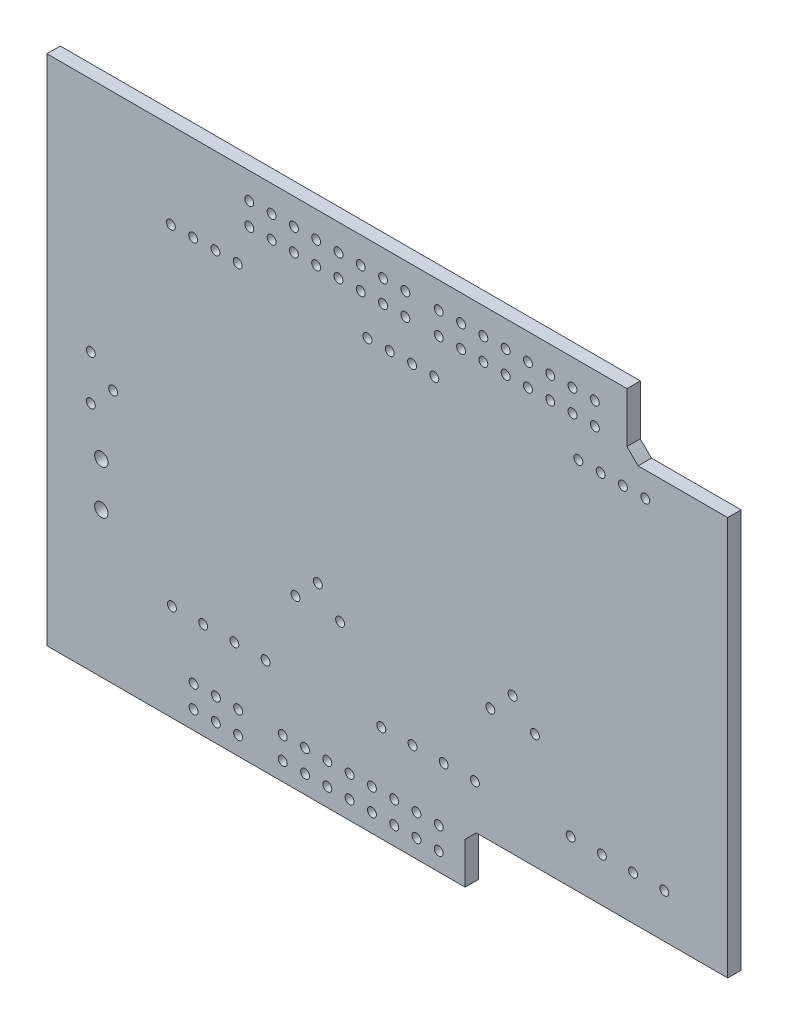
SolidWorks part; units mm, degrees
ref_plane "Front Plane" through (0, 0, 0) normal (0, 0, 1) x (1, 0, 0)
ref_plane "Top Plane" through (0, 0, 0) normal (0, 1, 0) x (1, 0, 0)
ref_plane "Right Plane" through (0, 0, 0) normal (1, 0, 0) x (0, 0, -1)
sketch "Sketch1" plane through (0, 0, 0) normal (0, 0, 1) x (1, 0, 0)
  line L1 (0, 0) -> (77.5716, 0)
  line L2 (0, 0) -> (0, 58.42)
  line L3 (0, 58.42) -> (77.5716, 58.42)
  line L4 (77.5716, 0) -> (77.5716, 58.42)
  dimension "D1" = 77.5716
  dimension "D2" = 58.42
extrude "Boss-Extrude1" add sketch "Sketch1" along normal blind 1.524
sketch "Sketch2" plane through (0, 0, 1.524) normal (0, 0, 1) x (1, 0, 0)
  line L1 (77.5716, 58.42) -> (66.0908, 58.42)
  line L2 (77.5716, 58.42) -> (77.5716, 51.435)
  line L3 (77.5716, 51.435) -> (66.0908, 51.435)
  line L4 (66.0908, 58.42) -> (66.0908, 51.435)
  line L5 (77.5716, 0) -> (47.6504, 0)
  line L6 (77.5716, 0) -> (77.5716, 6)
  line L7 (77.5716, 6) -> (47.6504, 6)
  line L8 (47.6504, 0) -> (47.6504, 6)
  dimension "D1" = 6
  dimension "D2" = 6.985
  dimension "D3" = 11.4808
  dimension "D4" = 29.9212
extrude "Cut-Extrude1" cut sketch "Sketch2" against normal through all
chamfer "Chamfer1" distance 1.27 angle 45 2 edges at (66.0908, 51.435, 0.762) (47.6504, 6, 0.762)
sketch "Sketch3" plane through (0, 0, 1.524) normal (0, 0, 1) x (1, 0, 0)
  line L0 (62.43, 52.88) -> (59.89, 52.88) construction
  line L1 (62.43, 52.88) -> (62.43, 55.42) construction
  line L4 (44.65, 4.62) -> (42.11, 4.62) construction
  line L5 (44.65, 2.08) -> (44.65, 4.62) construction
  line L7 (16.924, 11.2664) -> (11.5748, 10.7736) construction
  line L8 (38.501, 11.2664) -> (37.7002, 10.7664) construction
  line L9 (60.078, 11.2664) -> (59.2772, 10.7664) construction
  line L10 (6.6018, 22.0208) -> (5.8018, 21.0208) construction
  line L11 (5.8018, 21.0208) -> (5.8018, 17.0208) construction
  line L12 (6.6018, 16.0208) -> (5.8018, 17.0208) construction
  line L14 (60.5536, 48.6156) -> (63.0936, 48.6156) construction
  line L15 (14.2494, 11.02) -> (17.8054, 11.02) construction
  circle A0 centre (62.43, 52.88) radius 0.508
  circle A1 centre (59.89, 52.88) radius 0.508
  circle A2 centre (57.35, 52.88) radius 0.508
  circle A3 centre (54.81, 52.88) radius 0.508
  circle A4 centre (52.27, 52.88) radius 0.508
  circle A5 centre (49.73, 52.88) radius 0.508
  circle A6 centre (47.19, 52.88) radius 0.508
  circle A7 centre (44.65, 52.88) radius 0.508
  circle A8 centre (62.43, 55.42) radius 0.508
  circle A9 centre (59.89, 55.42) radius 0.508
  circle A10 centre (57.35, 55.42) radius 0.508
  circle A11 centre (54.81, 55.42) radius 0.508
  circle A12 centre (52.27, 55.42) radius 0.508
  circle A13 centre (49.73, 55.42) radius 0.508
  circle A14 centre (47.19, 55.42) radius 0.508
  circle A15 centre (44.65, 55.42) radius 0.508
  circle A16 centre (40.84, 52.88) radius 0.508
  circle A17 centre (38.3, 52.88) radius 0.508
  circle A18 centre (35.76, 52.88) radius 0.508
  circle A19 centre (33.22, 52.88) radius 0.508
  circle A20 centre (30.68, 52.88) radius 0.508
  circle A21 centre (28.14, 52.88) radius 0.508
  circle A22 centre (25.6, 52.88) radius 0.508
  circle A23 centre (23.06, 52.88) radius 0.508
  circle A24 centre (38.3, 55.42) radius 0.508
  circle A25 centre (35.76, 55.42) radius 0.508
  circle A26 centre (33.22, 55.42) radius 0.508
  circle A27 centre (30.68, 55.42) radius 0.508
  circle A28 centre (28.14, 55.42) radius 0.508
  circle A29 centre (25.6, 55.42) radius 0.508
  circle A30 centre (23.06, 55.42) radius 0.508
  circle A31 centre (40.84, 55.42) radius 0.508
  circle A32 centre (44.65, 4.62) radius 0.508
  circle A33 centre (42.11, 4.62) radius 0.508
  circle A34 centre (39.57, 4.62) radius 0.508
  circle A35 centre (37.03, 4.62) radius 0.508
  circle A36 centre (34.49, 4.62) radius 0.508
  circle A37 centre (31.95, 4.62) radius 0.508
  circle A38 centre (29.41, 4.62) radius 0.508
  circle A39 centre (26.87, 4.62) radius 0.508
  circle A40 centre (24.33, 4.62) radius 0.508 [skipped]
  circle A41 centre (21.79, 4.62) radius 0.508
  circle A42 centre (19.25, 4.62) radius 0.508
  circle A43 centre (16.71, 4.62) radius 0.508
  circle A44 centre (42.11, 2.08) radius 0.508
  circle A45 centre (39.57, 2.08) radius 0.508
  circle A46 centre (37.03, 2.08) radius 0.508
  circle A47 centre (34.49, 2.08) radius 0.508
  circle A48 centre (31.95, 2.08) radius 0.508
  circle A49 centre (29.41, 2.08) radius 0.508
  circle A50 centre (26.87, 2.08) radius 0.508
  circle A51 centre (24.33, 2.08) radius 0.508 [skipped]
  circle A52 centre (21.79, 2.08) radius 0.508
  circle A53 centre (19.25, 2.08) radius 0.508
  circle A54 centre (16.71, 2.08) radius 0.508
  circle A55 centre (44.65, 2.08) radius 0.508
  circle A56 centre (36.5252, 48.6156) radius 0.508
  circle A57 centre (60.5536, 48.6156) radius 0.508
  circle A58 centre (14.1224, 48.6156) radius 0.508
  circle A59 centre (14.2494, 11.02) radius 0.508
  circle A60 centre (38.1006, 11.0164) radius 0.508
  circle A61 centre (59.6776, 11.0164) radius 0.508
  circle A62 centre (6.2018, 21.5208) radius 0.762
  circle A63 centre (6.2018, 16.5208) radius 0.762
  circle A64 centre (63.0936, 48.6156) radius 0.508
  circle A65 centre (39.0652, 48.6156) radius 0.508
  circle A66 centre (16.6624, 48.6156) radius 0.508
  circle A67 centre (65.6336, 48.6156) radius 0.508
  circle A68 centre (41.6052, 48.6156) radius 0.508
  circle A69 centre (19.2024, 48.6156) radius 0.508
  circle A70 centre (68.1736, 48.6156) radius 0.508
  circle A71 centre (44.1452, 48.6156) radius 0.508
  circle A72 centre (21.7424, 48.6156) radius 0.508
  circle A73 centre (17.8054, 11.02) radius 0.508
  circle A74 centre (41.6566, 11.0164) radius 0.508
  circle A75 centre (63.2336, 11.0164) radius 0.508
  circle A76 centre (21.3614, 11.02) radius 0.508
  circle A77 centre (45.2126, 11.0164) radius 0.508
  circle A78 centre (66.7896, 11.0164) radius 0.508
  circle A79 centre (24.9174, 11.02) radius 0.508
  circle A80 centre (48.7686, 11.0164) radius 0.508
  circle A81 centre (70.3456, 11.0164) radius 0.508
  circle A82 centre (55.6026, 19.079) radius 0.508
  circle A83 centre (50.5226, 19.079) radius 0.508
  circle A84 centre (53.0626, 21.619) radius 0.508
  circle A85 centre (30.867, 21.619) radius 0.508
  circle A86 centre (33.407, 19.079) radius 0.508
  circle A87 centre (28.327, 19.079) radius 0.508
  circle A88 centre (5.0018, 26.418) radius 0.508
  circle A89 centre (7.5418, 28.958) radius 0.508
  circle A90 centre (5.0018, 31.498) radius 0.508
  dimension "D1" = 1.016
  dimension "D8" = 12
  dimension "D13" = 4
  dimension "D17" = 1.524
  dimension "D3" = 2.54
  dimension "D10" = 2.54
  dimension "D14" = 2.54
  dimension "D16" = 3.556
  dimension "D2" = 8
  dimension "D4" = 2
  dimension "D9" = 2
  dimension "D15" = 4
extrude "Cut-Extrude2" cut sketch "Sketch3" against normal through all
